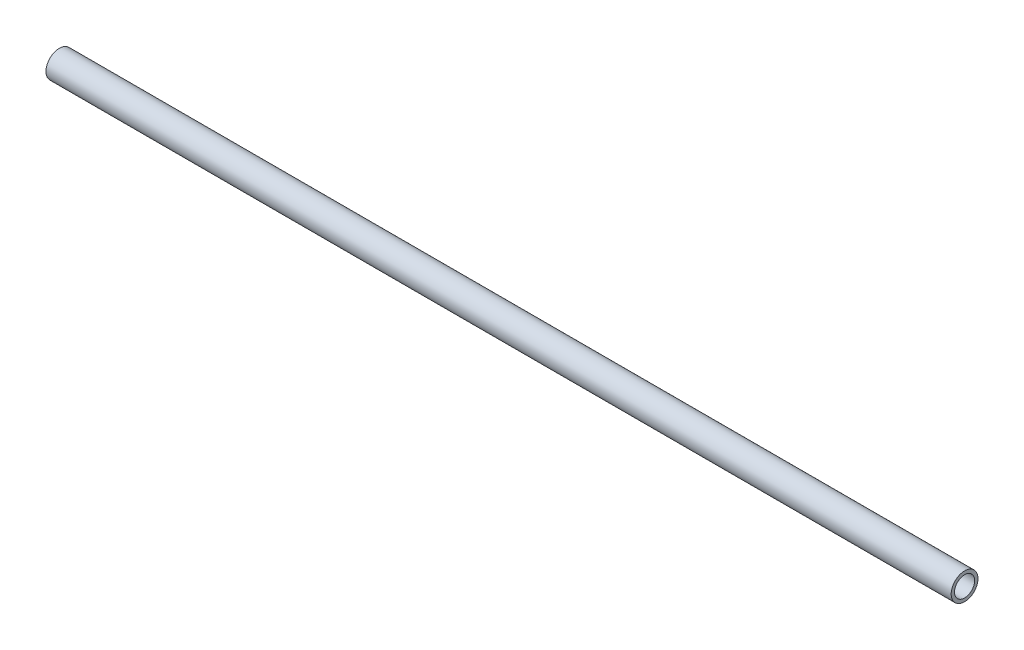
SolidWorks part; units mm, degrees
material "Aluminium"
ref_plane "Front Plane" through (0, 0, 0) normal (0, 0, 1) x (1, 0, 0)
ref_plane "Top Plane" through (0, 0, 0) normal (0, 1, 0) x (1, 0, 0)
ref_plane "Right Plane" through (0, 0, 0) normal (1, 0, 0) x (0, 0, -1)
sketch "Sketch1" plane through (0, 0, 0) normal (1, 0, 0) x (0, 0, -1)
  circle A0 centre (0, 0) radius 4
  circle A1 centre (0, 0) radius 3
  dimension "D1" = 8
  dimension "D2" = 1
extrude "Boss-Extrude1" add sketch "Sketch1" along normal mid plane 270
